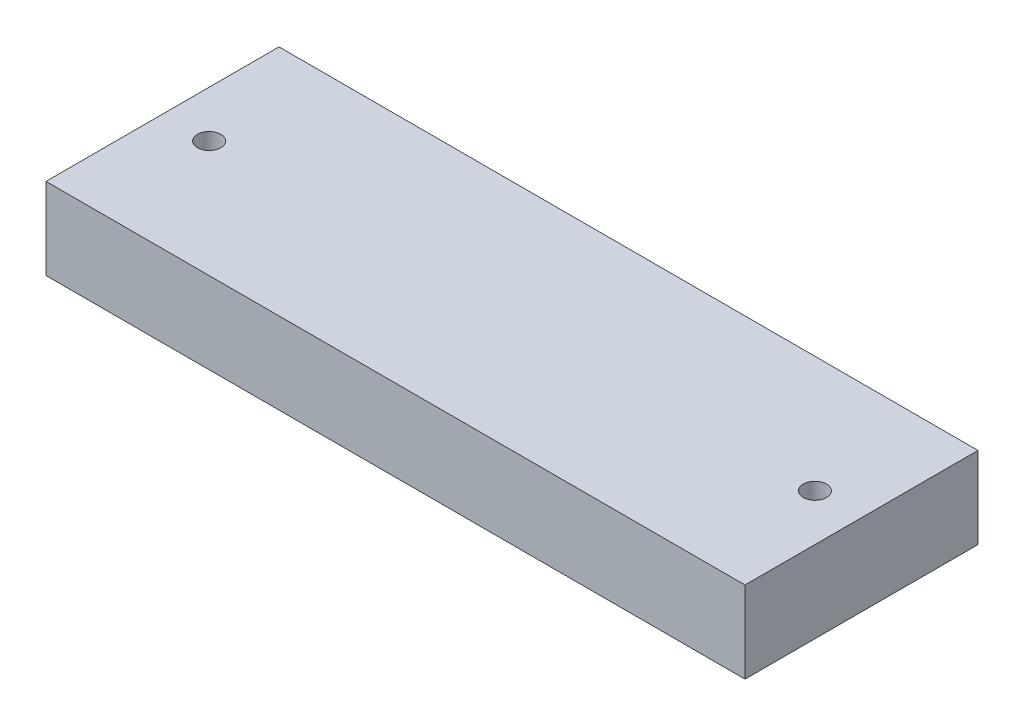
SolidWorks part; units mm, degrees
ref_plane "Front Plane" through (0, 0, 0) normal (0, 0, 1) x (1, 0, 0)
ref_plane "Top Plane" through (0, 0, 0) normal (0, 1, 0) x (1, 0, 0)
ref_plane "Right Plane" through (0, 0, 0) normal (1, 0, 0) x (0, 0, -1)
sketch "Sketch1" plane through (0, 0, 0) normal (0, 1, 0) x (1, 0, 0)
  line L1 (-150, 50) -> (150, 50)
  line L2 (-150, 50) -> (-150, -50)
  line L3 (-150, -50) -> (150, -50)
  line L4 (150, 50) -> (150, -50)
  line L5 (-150, 50) -> (150, -50) construction
  line L6 (-150, -50) -> (150, 50) construction
  point P0 (0, 0)
  dimension "D1" = 300
  dimension "D2" = 100
extrude "Boss-Extrude1" add sketch "Sketch1" along normal blind 35
sketch "Sketch2" plane through (0, 35, 0) normal (0, 1, 0) x (1, 0, 0)
  line L0 (-150, 50) -> (-150, -50) construction
  line L1 (0, 50) -> (0, -50) construction
  line L2 (-150, -50) -> (150, -50) construction
  circle A0 centre (-130, 0) radius 5
  circle A1 centre (130, 0) radius 5
  point P11 (0, 0)
  dimension "D1" = 10
  dimension "D2" = 20
extrude "Cut-Extrude1" cut sketch "Sketch2" against normal through all
